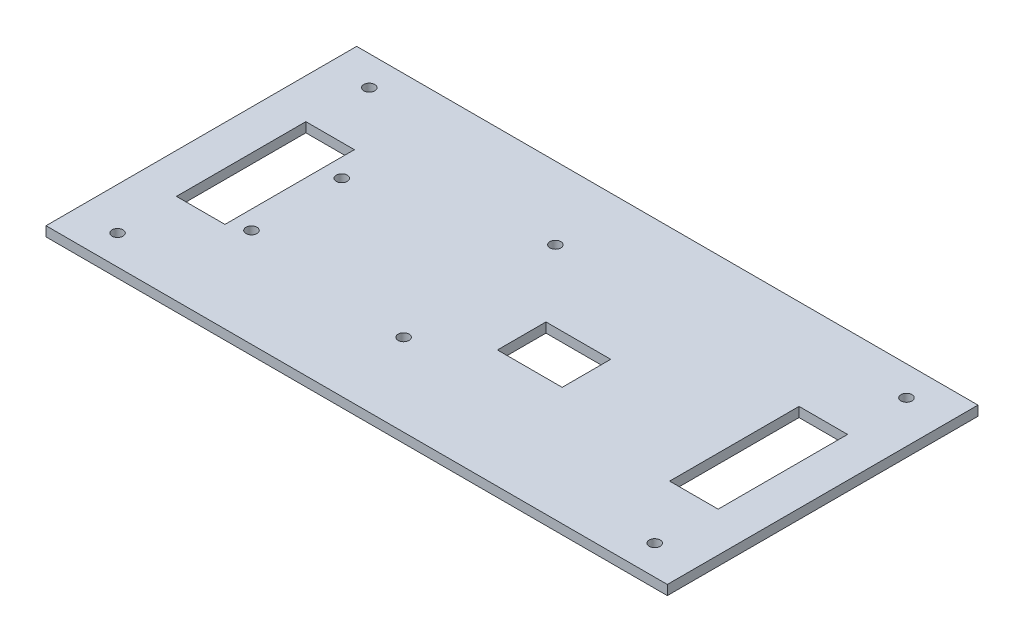
SolidWorks part; units mm, degrees
ref_plane "Front Plane" through (0, 0, 0) normal (0, 0, 1) x (1, 0, 0)
ref_plane "Top Plane" through (0, 0, 0) normal (0, 1, 0) x (1, 0, 0)
ref_plane "Right Plane" through (0, 0, 0) normal (1, 0, 0) x (0, 0, -1)
sketch "Sketch1" plane through (0, 0, 0) normal (0, 1, 0) x (1, 0, 0)
  line L1 (0, 0) -> (192, 0)
  line L2 (0, 0) -> (0, 96)
  line L3 (0, 96) -> (192, 96)
  line L4 (192, 0) -> (192, 96)
  dimension "D1" = 192
  dimension "D2" = 96
extrude "Boss-Extrude1" add sketch "Sketch1" along normal blind 3
hole_wizard "M3 Clearance Hole1" positions "Sketch3" profile "Sketch5" hole size "M3" standard "ANSI Metric" end condition through all
sketch "Sketch3" plane through (0, 0, 0) normal (0, -1, 0) x (-1, 0, 0)
  line L0 (0, 0) -> (-192, 0) construction
  line L1 (0, 96) -> (0, 0) construction
  line L2 (-192, 96) -> (0, 96) construction
  line L3 (-192, 0) -> (-192, 96) construction
  point P0 (-13, 9.1)
  point P4 (-179, 9.1)
  point P6 (-179, 86.9)
  point P10 (-13, 86.9)
  point P21 (0, 0)
  point P22 (0, 0)
  dimension "D1" = 9.1
  dimension "D2" = 13
  dimension "D3" = 13
  dimension "D4" = 9.1
  dimension "D7" = 9.1
  dimension "D8" = 9.1
  dimension "D9" = 13
  dimension "D10" = 13
sketch "Sketch5" plane through (13, 0, -9.1) normal (1, 0, 0) x (0, 0, -1)
  line L0 (0, 0) -> (0, 3)
  line L1 (0, 3) -> (1.7, 3)
  line L2 (1.7, 3) -> (1.7, 0)
  line L5 (1.7, 0) -> (0, 0)
  line L11 (0, -6.35) -> (0, 107.95) construction
  dimension "Thru Hole Dia." = 3.4
  dimension "Thru Hole Depth" = 3
sketch "Sketch6" plane through (0, 0, 0) normal (0, -1, 0) x (1, 0, 0)
  line L0 (0, -96) -> (0, 0) construction
  line L1 (12.3, -28) -> (27.3, -28)
  line L2 (12.3, -28) -> (12.3, -68)
  line L3 (12.3, -68) -> (27.3, -68)
  line L4 (27.3, -28) -> (27.3, -68)
  line L5 (192, -96) -> (0, -96) construction
  line L6 (192, 0) -> (192, -96) construction
  line L7 (179.7, -28) -> (164.7, -28)
  line L8 (179.7, -28) -> (179.7, -68)
  line L9 (179.7, -68) -> (164.7, -68)
  line L10 (164.7, -28) -> (164.7, -68)
  line L12 (103, -36.5) -> (123, -36.5)
  line L13 (103, -36.5) -> (103, -51.5)
  line L14 (103, -51.5) -> (123, -51.5)
  line L15 (123, -36.5) -> (123, -51.5)
  dimension "D1" = 15
  dimension "D2" = 40
  dimension "D3" = 12.3
  dimension "D4" = 28
  dimension "D5" = 15
  dimension "D6" = 40
  dimension "D7" = 28
  dimension "D8" = 12.3
  dimension "D9" = 20
  dimension "D10" = 15
  dimension "D11" = 103
  dimension "D12" = 44.5
extrude "Cut-Extrude1" cut sketch "Sketch6" against normal through all
hole_wizard "M3 Clearance Hole2" positions "Sketch7" profile "Sketch8" hole size "M3" standard "ANSI Metric" end condition through all
sketch "Sketch7" plane through (0, 0, 0) normal (0, -1, 0) x (-1, 0, 0)
  line L0 (0, 96) -> (0, 0) construction
  line L1 (-192, 96) -> (0, 96) construction
  point P0 (-33, 58.4)
  point P2 (-33, 30.5)
  point P4 (-85.11, 25.4)
  point P6 (-83.8, 73.6)
  dimension "D1" = 33
  dimension "D2" = 37.6
  dimension "D3" = 27.9
  dimension "D4" = 15.2
  dimension "D5" = 50.8
  dimension "D6" = 5.1
  dimension "D7" = 52.11
  dimension "D8" = 1.31
sketch "Sketch8" plane through (33, 0, -58.4) normal (1, 0, 0) x (0, 0, -1)
  line L0 (0, 0) -> (0, 3)
  line L1 (0, 3) -> (1.7, 3)
  line L2 (1.7, 3) -> (1.7, 0)
  line L5 (1.7, 0) -> (0, 0)
  line L11 (0, -6.35) -> (0, 107.95) construction
  dimension "Thru Hole Dia." = 3.4
  dimension "Thru Hole Depth" = 3
